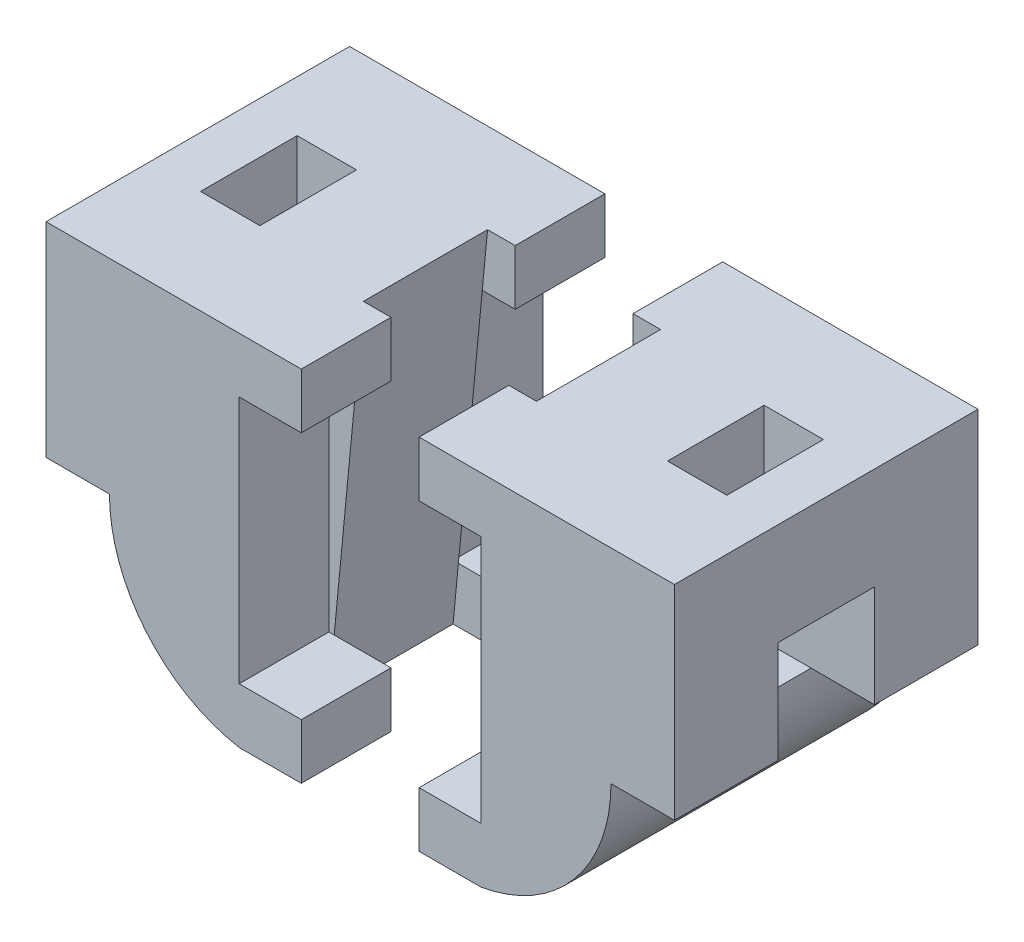
SolidWorks part; units mm, degrees
ref_plane "정면" through (0, 0, 0) normal (0, 0, 1) x (1, 0, 0)
ref_plane "윗면" through (0, 0, 0) normal (0, 1, 0) x (1, 0, 0)
ref_plane "우측면" through (0, 0, 0) normal (1, 0, 0) x (0, 0, -1)
sketch "스케치2" plane through (-51.3677, 0, 0) normal (0, 0, 1) x (1, 0, 0)
  line L7 (80.9084, -179.4529) -> (68.9084, -179.4529)
  line L8 (80.9084, -179.4529) -> (80.9084, -209.0445)
  line L25 (80.9084, -209.0445) -> (87.714, -209.0445)
  line L26 (68.9084, -179.4529) -> (68.9084, -231.4529)
  arc A5 (87.714, -209.0445) -> (68.9084, -231.4529) centre (64.9604, -209.0445) cw
  point P674 (77.5869, -197.1281)
  dimension "D1" = 12
  dimension "D2" = 52
extrude "보스-돌출1" add sketch "스케치2" against normal blind 29 and the other way blind 15
sketch "스케치7" plane through (29.5407, 0, 0) normal (1, 0, 0) x (0, 0, -1)
  line L0 (-15, -179.4529) -> (0, -179.4529)
  line L1 (-15, -179.4529) -> (29, -179.4529) construction
  line L2 (0, -179.4529) -> (0, -209.0445)
  line L4 (0, -209.0445) -> (-15, -209.0445)
  line L5 (-15, -209.0445) -> (-15, -179.4529)
  line L6 (29, -179.4529) -> (29, -209.0445)
  line L7 (29, -209.0445) -> (14, -209.0445)
  line L8 (14, -209.0445) -> (14, -179.4529)
  line L9 (14, -179.4529) -> (29, -179.4529)
  dimension "D1" = 15
  dimension "D2" = 15
extrude "보스-돌출3" add sketch "스케치7" along normal blind 16
sketch "스케치11" plane through (-11.9225, 0, -14) normal (0, 0, 1) x (1, 0, 0)
  line L7 (57.4631, -179.4529) -> (57.4631, -209.0445) construction
  line L8 (57.4631, -194.2487) -> (57.4631, -179.4529)
  line L10 (57.4631, -179.4529) -> (50.0631, -179.4529)
  line L11 (57.4631, -179.4529) -> (41.4631, -179.4529) construction
  line L12 (50.0631, -179.4529) -> (50.0631, -194.2487)
  line L13 (50.0631, -194.2487) -> (57.4631, -194.2487)
extrude "보스-돌출13" add sketch "스케치11" along normal up to surface (14 mm away) contours L8 L10 L12 L13 up to face at (37.3018, -197.2079, 0)
sketch "스케치13" plane through (17.5407, 0, 0) normal (-1, 0, 0) x (0, 0, 1)
  line L0 (15, -179.4529) -> (2, -179.4529)
  line L1 (15, -179.4529) -> (-29, -179.4529) construction
  line L2 (2, -179.4529) -> (2, -187.4529)
  line L3 (2, -187.4529) -> (15, -187.4529)
  line L4 (15, -179.4529) -> (15, -231.4529) construction
  line L5 (15, -187.4529) -> (15, -179.4529)
  line L6 (-29, -179.4529) -> (-29, -187.4529)
  line L7 (-29, -179.4529) -> (-29, -231.4529) construction
  line L8 (-29, -187.4529) -> (-16, -187.4529)
  line L9 (-16, -187.4529) -> (-16, -179.4529)
  line L10 (-16, -179.4529) -> (-29, -179.4529)
  line L11 (-29, -231.4529) -> (-16, -231.4529)
  line L12 (15, -231.4529) -> (-29, -231.4529) construction
  line L13 (-16, -231.4529) -> (-16, -223.4529)
  line L14 (-16, -223.4529) -> (-29, -223.4529)
  line L15 (-29, -223.4529) -> (-29, -231.4529)
  line L16 (2, -231.4529) -> (15, -231.4529)
  line L17 (15, -231.4529) -> (15, -223.4529)
  line L18 (15, -223.4529) -> (2, -223.4529)
  line L19 (2, -231.4529) -> (2, -223.4529)
extrude "보스-돌출16" add sketch "스케치13" along normal blind 9
sketch "스케치14" plane through (0, 0, -16) normal (0, 0, 1) x (1, 0, 0)
  line L0 (17.5407, -179.4529) -> (12.5407, -179.4529)
  line L2 (12.5407, -179.4529) -> (17.5407, -231.4529)
  line L3 (17.5407, -231.4529) -> (17.5407, -179.4529)
extrude "보스-돌출17" add sketch "스케치14" along normal up to surface (18 mm away) up to face at (13.0407, -183.4529, 2)
mirror "대칭 복사2" about plane through (0, 0, 0) normal (1, 0, 0) of bodies 124 110 118
